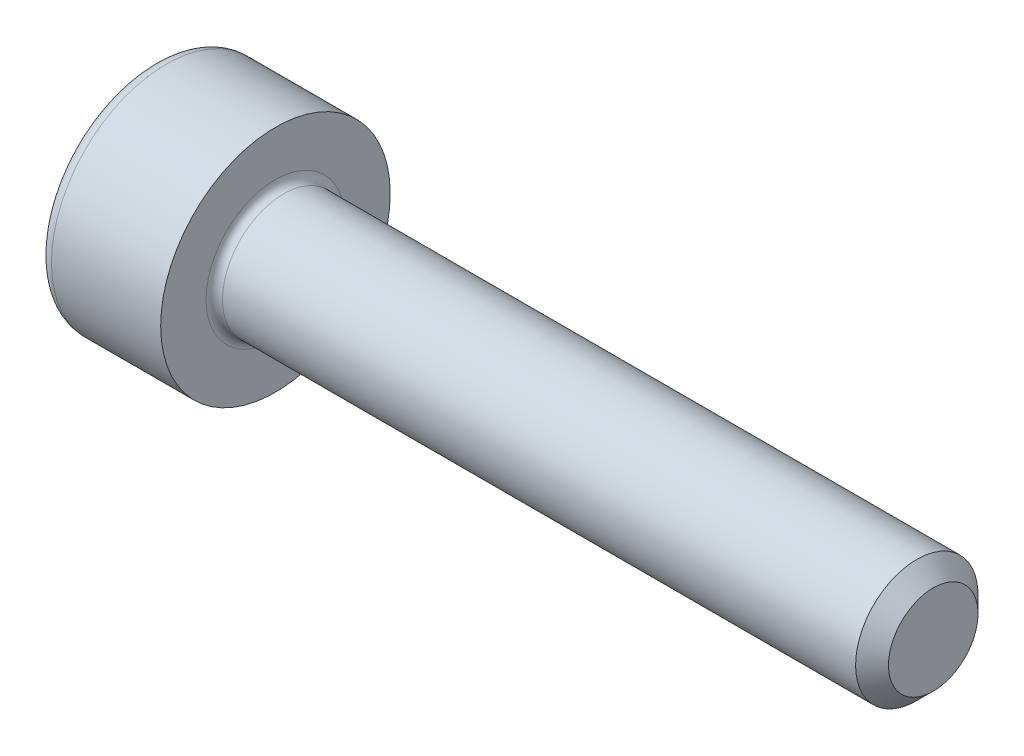
SolidWorks part; units mm, degrees
ref_plane "Спереди" through (0, 0, 0) normal (0, 0, 1) x (1, 0, 0)
ref_plane "Сверху" through (0, 0, 0) normal (0, 1, 0) x (1, 0, 0)
ref_plane "Справа" through (0, 0, 0) normal (1, 0, 0) x (0, 0, -1)
sketch "Sketch1" plane through (0, 0, 0) normal (0, 0, 1) x (1, 0, 0)
  line L0 (0, 0) -> (1.4887, 0)
  line L1 (1.4887, 0) -> (1.4887, 1.3957)
  line L2 (1.4887, 1.3957) -> (0, 1.3957)
  line L3 (0, 1.3957) -> (0, 0)
  line L4 (1.4887, 0) -> (9.4887, 0)
  line L5 (9.4887, 0) -> (9.4887, 0.7444)
  line L6 (9.4887, 0.7444) -> (1.4887, 0.7444)
  dimension "D1" = 8
revolve "Revolve1" add sketch "Sketch1" angle 360 about L0
fillet "Fillet1" radius 0.1 1 edges at (1.4887, 0, 0.7444)
fillet "Fillet2" radius 0.16 1 edges at (0, 0, 1.3957)
chamfer "Chamfer1" distance 0.2 angle 45 1 edges at (9.4887, 0, 0.7444)
sketch "Sketch2" plane through (0, 0, 0) normal (-1, 0, 0) x (0, 0, 1)
  line L1 (0, 0.8776) -> (-0.76, 0.4388)
  line L2 (-0.76, 0.4388) -> (-0.76, -0.4388)
  line L3 (-0.76, -0.4388) -> (0, -0.8776)
  line L4 (0, -0.8776) -> (0.76, -0.4388)
  line L5 (0.76, -0.4388) -> (0.76, 0.4388)
  line L6 (0.76, 0.4388) -> (0, 0.8776)
  circle A0 centre (0, 0) radius 0.76 construction
extrude "Extrude1" cut sketch "Sketch2" against normal blind 0.7
